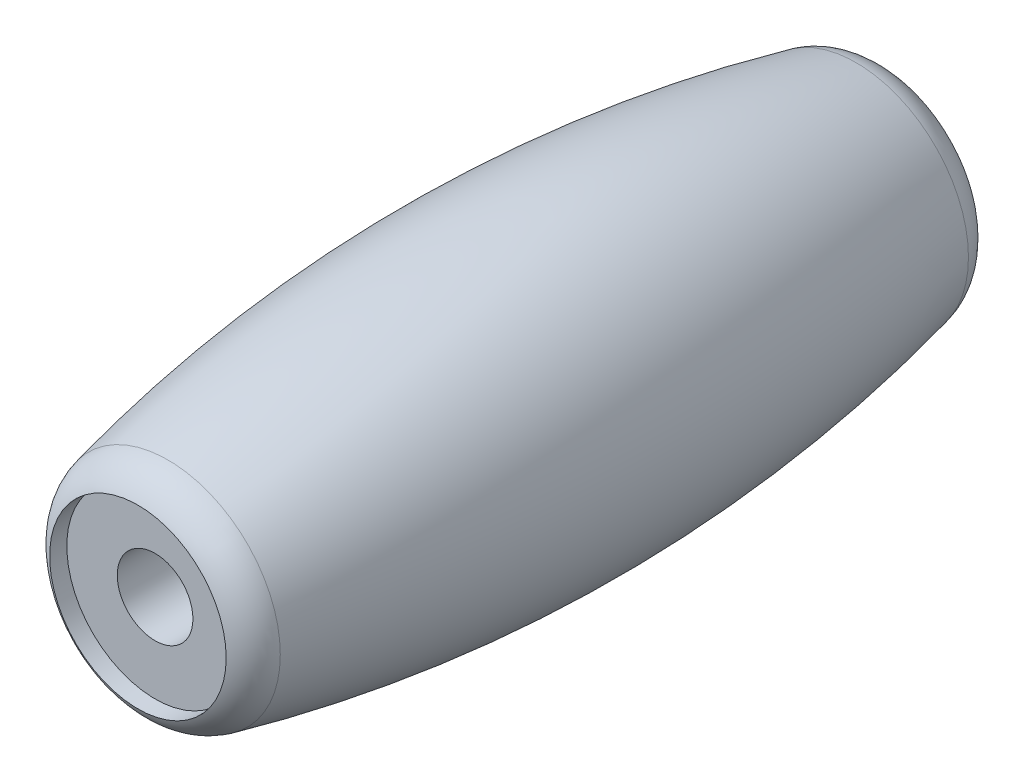
SolidWorks part; units mm, degrees
ref_plane "Front Plane" through (0, 0, 0) normal (0, 0, 1) x (1, 0, 0)
ref_plane "Top Plane" through (0, 0, 0) normal (0, 1, 0) x (1, 0, 0)
ref_plane "Right Plane" through (0, 0, 0) normal (1, 0, 0) x (0, 0, -1)
sketch "Sketch1" plane through (0, 0, 0) normal (1, 0, 0) x (0, 0, -1)
  line L0 (-15, 0) -> (15, 0) construction
  line L1 (0, 0) -> (0, 6) construction
  line L2 (15, 0) -> (15, 2.75) construction
  line L3 (-15, 0) -> (-15, 2.75) construction
  line L4 (15, 2.75) -> (13.25, 2.75) construction
  line L5 (-15, 2.75) -> (-13.25, 2.75) construction
  line L6 (14.15, 1.5) -> (-14.15, 1.5)
  line L7 (14.15, 1.5) -> (14.15, 3.5)
  line L8 (-14.15, 1.5) -> (-14.15, 3.5)
  line L9 (14.15, 3.5) -> (14.8311, 3.5)
  line L10 (-14.15, 3.5) -> (-14.8311, 3.5)
  arc A0 (14.8311, 3.5) -> (15, 2.75) centre (13.25, 2.75) ccw construction
  arc A1 (-14.8311, 3.5) -> (-15, 2.75) centre (-13.25, 2.75) cw construction
  arc A2 (-13.6412, 4.4557) -> (13.6412, 4.4557) centre (0, -55.0208) cw
  arc A3 (13.6412, 4.4557) -> (14.8311, 3.5) centre (13.25, 2.75) cw
  arc A4 (-14.8311, 3.5) -> (-13.6412, 4.4557) centre (-13.25, 2.75) cw
  point P4 (0, 0)
  point P26 (14.4906, 3.5)
  dimension "D1" = 30
  dimension "D2" = 6
  dimension "D3" = 2.75
  dimension "D4" = 1.75
  dimension "D5" = 1.5
  dimension "D6" = 3.5
  dimension "D7" = 0.85
revolve "Revolve1" add sketch "Sketch1" angle 360 about L0
